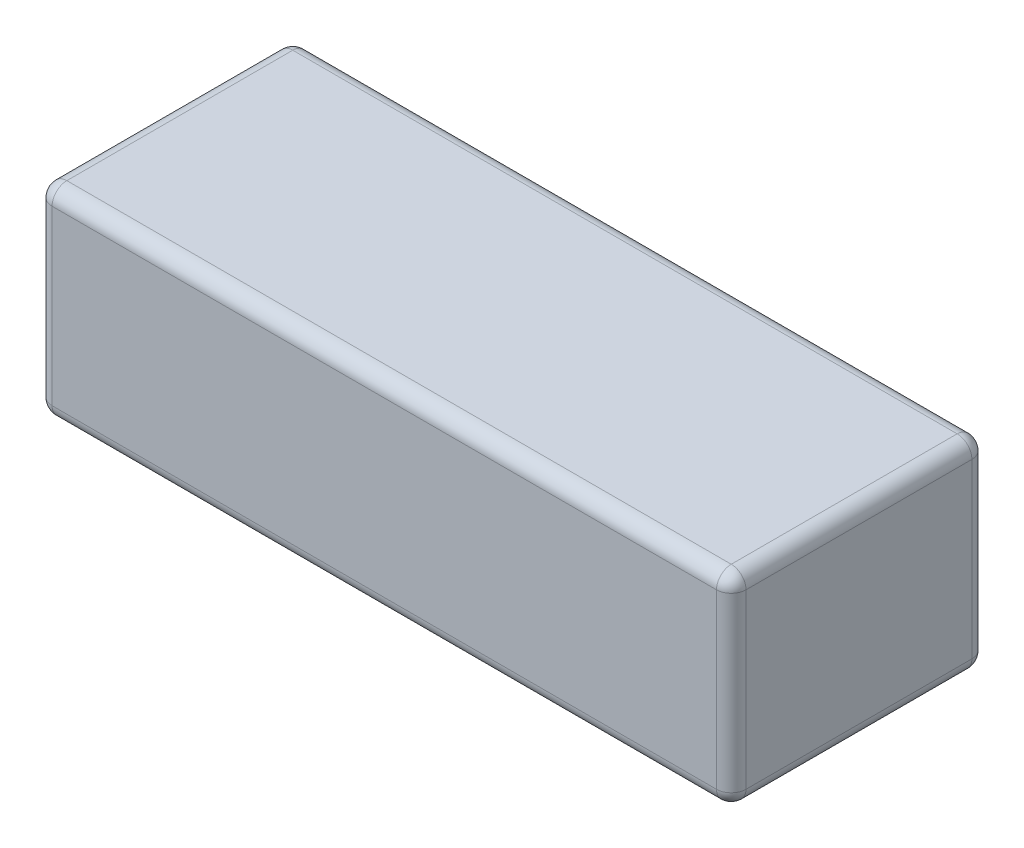
SolidWorks part; units mm, degrees
ref_plane "Front Plane" through (0, 0, 0) normal (0, 0, 1) x (1, 0, 0)
ref_plane "Top Plane" through (0, 0, 0) normal (0, 1, 0) x (1, 0, 0)
ref_plane "Right Plane" through (0, 0, 0) normal (1, 0, 0) x (0, 0, -1)
sketch "Sketch1" plane through (0, 0, 0) normal (0, 1, 0) x (1, 0, 0)
  line L1 (-23.5, -8.65) -> (23.5, -8.65)
  line L2 (-23.5, -8.65) -> (-23.5, 8.65)
  line L3 (-23.5, 8.65) -> (23.5, 8.65)
  line L4 (23.5, -8.65) -> (23.5, 8.65)
  line L5 (0, 8.65) -> (0, -8.65) construction
  line L6 (-23.5, 0) -> (23.5, 0) construction
  point P0 (0, 0)
  dimension "D1" = 47
  dimension "D2" = 17.3
extrude "Boss-Extrude1" add sketch "Sketch1" along normal blind 13.7
fillet "Fillet1" radius 1 12 edges at (23.5, 0, 0) (0, 0, 8.65) (23.5, 13.7, 0) (0, 13.7, -8.65) (-23.5, 13.7, 0) (0, 13.7, 8.65) (23.5, 6.85, 8.65) (-23.5, 6.85, 8.65) (23.5, 6.85, -8.65) (-23.5, 0, 0) (-23.5, 6.85, -8.65) (0, 0, -8.65)
